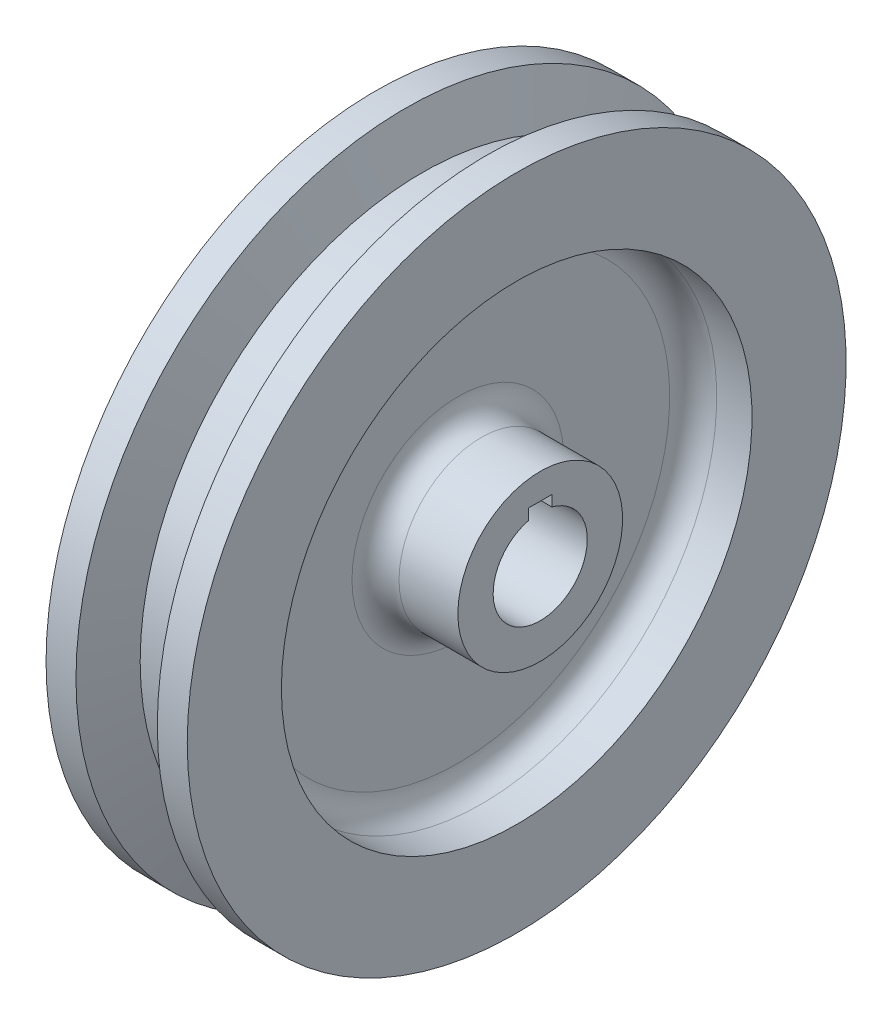
SolidWorks part; units mm, degrees
ref_plane "Front Plane" through (0, 0, 0) normal (0, 0, 1) x (1, 0, 0)
ref_plane "Top Plane" through (0, 0, 0) normal (0, 1, 0) x (1, 0, 0)
ref_plane "Right Plane" through (0, 0, 0) normal (1, 0, 0) x (0, 0, -1)
sketch "Sketch1" plane through (0, 0, 0) normal (0, 0, 1) x (1, 0, 0)
  line L0 (0, 42.0511) -> (0, -40.7341) construction
  line L1 (-43.2741, -12.7) -> (43.2741, -12.7) construction
  line L2 (-25.4, 0) -> (25.4, 0)
  line L3 (25.4, 0) -> (25.4, 9.525)
  line L4 (25.4, 9.525) -> (9.525, 9.525)
  line L5 (3.175, 15.875) -> (3.175, 44.45)
  line L6 (9.525, 50.8) -> (19.05, 50.8)
  line L7 (19.05, 50.8) -> (19.05, 76.2)
  line L8 (19.05, 76.2) -> (10.9724, 76.2)
  line L9 (10.9724, 76.2) -> (6.35, 63.5)
  line L10 (6.35, 63.5) -> (-6.35, 63.5)
  line L11 (-6.35, 63.5) -> (-10.9724, 76.2)
  line L12 (-10.9724, 76.2) -> (-19.05, 76.2)
  line L13 (-19.05, 76.2) -> (-19.05, 50.8)
  line L14 (-19.05, 50.8) -> (-9.525, 50.8)
  line L15 (-3.175, 44.45) -> (-3.175, 15.875)
  line L16 (-9.525, 9.525) -> (-25.4, 9.525)
  line L17 (-25.4, 9.525) -> (-25.4, 0)
  arc A0 (9.525, 9.525) -> (3.175, 15.875) centre (9.525, 15.875) cw
  arc A1 (-9.525, 9.525) -> (-3.175, 15.875) centre (-9.525, 15.875) ccw
  arc A2 (3.175, 44.45) -> (9.525, 50.8) centre (9.525, 44.45) cw
  arc A3 (-3.175, 44.45) -> (-9.525, 50.8) centre (-9.525, 44.45) ccw
  point P5 (0, -12.7)
  point P8 (0, 0)
  point P29 (3.175, 50.8)
  dimension "D11" = 6.35
  dimension "D1" = 50.8
  dimension "D2" = 12.7
  dimension "D3" = 40
  dimension "D4" = 25.4
  dimension "D5" = 38.1
  dimension "D6" = 127
  dimension "D7" = 44.45
  dimension "D8" = 177.8
  dimension "D9" = 12.7
  dimension "D10" = 6.35
revolve "Revolve1" add sketch "Sketch1" angle 360 about L1
sketch "Sketch2" plane through (0, 0, 0) normal (1, 0, 0) x (0, 0, -1)
  line L0 (0, 79.0791) -> (0, -20.0198) construction
  line L1 (-3.175, -0.4033) -> (-3.175, 2.54)
  line L2 (-3.175, 2.54) -> (3.175, 2.54)
  line L3 (3.175, 2.54) -> (3.175, -0.4033)
  line L4 (-3.175, -0.4033) -> (3.175, -0.4033)
  circle A0 centre (0, -12.7) radius 12.7 construction
  dimension "D1" = 6.35
  dimension "D2" = 15.24
extrude "Cut-Extrude1" cut sketch "Sketch2" against normal through all both and the other way through all contours L4 L3 L2 L1
